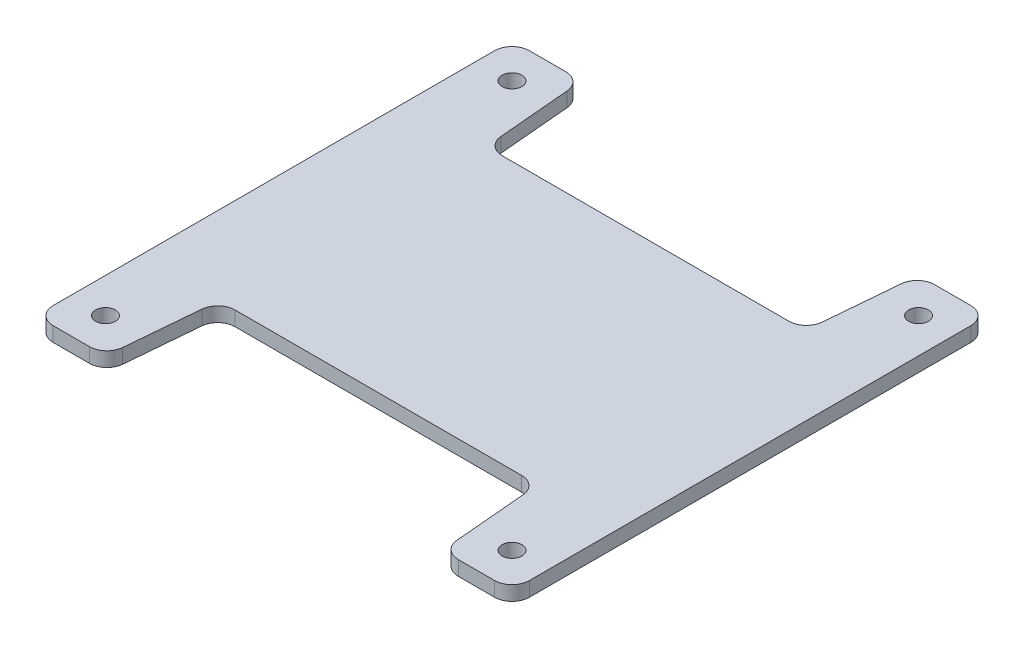
SolidWorks part; units mm, degrees
material "Thornel Mat VMA"
ref_plane "Front Plane" through (0, 0, 0) normal (0, 0, 1) x (1, 0, 0)
ref_plane "Top Plane" through (0, 0, 0) normal (0, 1, 0) x (1, 0, 0)
ref_plane "Right Plane" through (0, 0, 0) normal (1, 0, 0) x (0, 0, -1)
sketch "Sketch1" plane through (0, 0, 0) normal (0, 1, 0) x (1, 0, 0)
  line L0 (-41, 41) -> (41, 41)
  line L1 (-35, 35) -> (35, 35) construction
  line L2 (-35, 35) -> (-35, -35) construction
  line L3 (-35, -35) -> (35, -35) construction
  line L4 (35, 35) -> (35, -35) construction
  line L5 (-35, 35) -> (35, -35) construction
  line L6 (-35, -35) -> (35, 35) construction
  line L7 (41, 41) -> (41, -41)
  line L8 (-41, -41) -> (41, -41)
  line L9 (-41, 41) -> (-41, -41)
  point P0 (0, 0)
  dimension "D1" = 70
  dimension "D2" = 70
  dimension "D3" = 6
extrude "Boss-Extrude1" add sketch "Sketch1" along normal mid plane 2.5
hole_wizard "M3 Clearance Hole1" positions "Sketch2" profile "Sketch3" hole size "M3" standard "ANSI Metric" end condition through all
sketch "Sketch2" plane through (0, 1.25, 0) normal (0, 1, 0) x (1, 0, 0)
  line L1 (-35, -35) -> (35, -35) construction
  line L2 (-35, -35) -> (-35, 35) construction
  line L3 (-35, 35) -> (35, 35) construction
  line L4 (35, -35) -> (35, 35) construction
  line L5 (-35, -35) -> (35, 35) construction
  line L6 (-35, 35) -> (35, -35) construction
  point P2 (35, 35)
  point P83 (-35, -35)
  point P84 (-35, 35)
  point P85 (35, -35)
  dimension "D1" = 70
sketch "Sketch3" plane through (35, 1.25, -35) normal (1, 0, 0) x (0, 0, 1)
  line L0 (0, 0) -> (0, 2.5)
  line L1 (0, 2.5) -> (1.7, 2.5)
  line L2 (1.7, 2.5) -> (1.7, 0)
  line L5 (1.7, 0) -> (0, 0)
  line L11 (0, -6.35) -> (0, 107.95) construction
  dimension "Thru Hole Dia." = 3.4
  dimension "Thru Hole Depth" = 2.5
sketch "Sketch4" plane through (0, -1.25, 0) normal (0, -1, 0) x (-1, 0, 0)
  line L0 (-29, 41) -> (-27.4252, 23)
  line L1 (-41, 41) -> (41, 41) construction
  line L2 (-27.4252, 23) -> (27.4252, 23)
  line L3 (0, 0) -> (0, 23)
  line L4 (29, 41) -> (27.4252, 23)
  line L5 (0, 0) -> (29, 0) construction
  line L6 (29, -41) -> (27.4252, -23)
  line L7 (-27.4252, -23) -> (27.4252, -23)
  line L8 (-29, -41) -> (-27.4252, -23)
  line L9 (-29, 41) -> (29, 41)
  line L10 (-29, -41) -> (29, -41)
  circle A0 centre (-35, 35) radius 1.7 construction
  line M11 (41, 41) -> (-41, 41)
  line M15 (-41, -41) -> (41, -41)
  dimension "D3" = 6
  dimension "D1" = 23
  dimension "D2" = 95
extrude "Cut-Extrude1" cut sketch "Sketch4" against normal through all contours L8 L6 L7 M15 | L4 L0 L2 M11
fillet "Fillet1" radius 3 12 edges at (41, 0, -41) (-41, 0, -41) (-41, 0, 41) (41, 0, 41) (-27.4252, 0, 23) (-29, 0, -41) (-27.4252, 0, -23) (27.4252, 0, -23) (29, 0, -41) (29, 0, 41) (27.4252, 0, 23) (-29, 0, 41)
